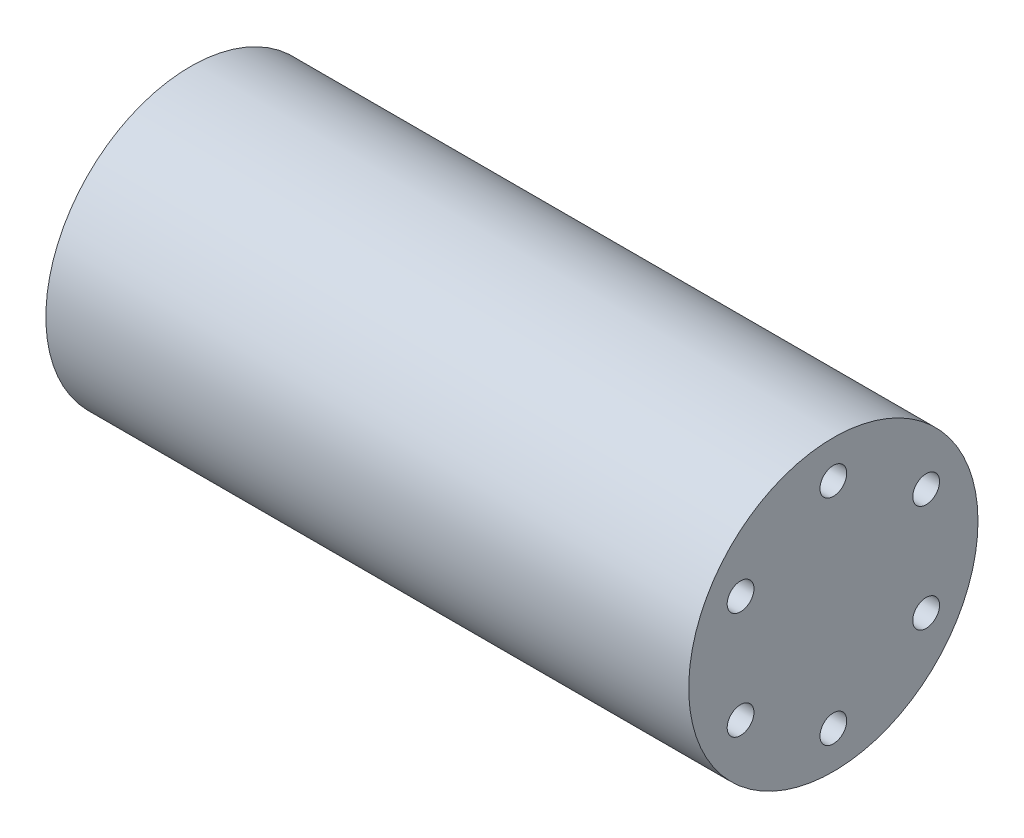
SolidWorks part; units mm, degrees
ref_plane "Front Plane" through (0, 0, 0) normal (0, 0, 1) x (1, 0, 0)
ref_plane "Top Plane" through (0, 0, 0) normal (0, 1, 0) x (1, 0, 0)
ref_plane "Right Plane" through (0, 0, 0) normal (1, 0, 0) x (0, 0, -1)
sketch "Sketch1" plane through (0, 0, 0) normal (1, 0, 0) x (0, 0, -1)
  circle A0 centre (0, 0) radius 13.5
  dimension "D1" = 27
extrude "Boss-Extrude1" add sketch "Sketch1" along normal mid plane 60
sketch "Sketch2" plane through (-30, 0, 0) normal (-1, 0, 0) x (0, 0, 1)
  circle A0 centre (0, 10) radius 1.25
  circle A1 centre (0, 0) radius 13.5 construction
  circle A2 centre (8.6603, 5) radius 1.25
  circle A3 centre (8.6603, -5) radius 1.25
  circle A4 centre (0, -10) radius 1.25
  circle A5 centre (-8.6603, -5) radius 1.25
  circle A6 centre (-8.6603, 5) radius 1.25
  point P17 (0, 0)
  dimension "D1" = 2.5
  dimension "D2" = 10
  dimension "D3" = 6
extrude "Cut-Extrude1" cut sketch "Sketch2" against normal blind 4
mirror "Mirror1" about plane through (0, 0, 0) normal (1, 0, 0) of "Cut-Extrude1"
scale "Scale1" scale about centroid uniform scaling yes scale factor 0.5
